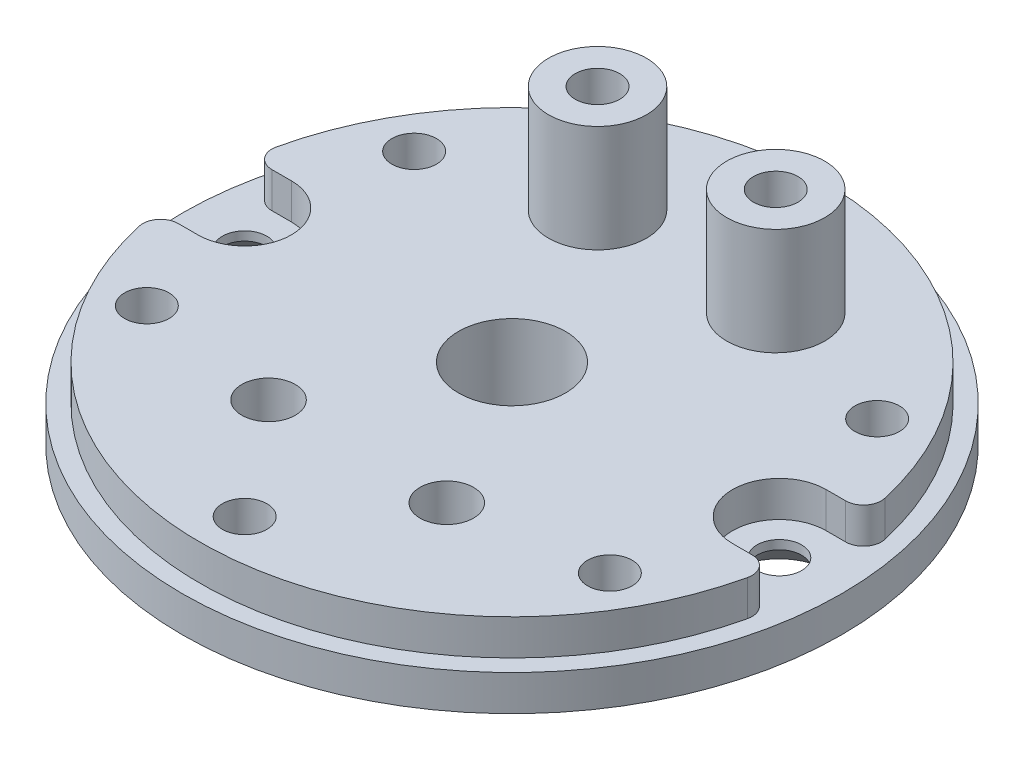
SolidWorks part; units mm, degrees
material "AISI 1020 Steel, Cold Rolled"
ref_plane "Front" through (0, 0, 0) normal (0, 0, 1) x (1, 0, 0)
ref_plane "Top" through (0, 0, 0) normal (0, 1, 0) x (1, 0, 0)
ref_plane "Right" through (0, 0, 0) normal (1, 0, 0) x (0, 0, -1)
sketch "Sketch1" plane through (0, 0, 0) normal (0, 1, 0) x (1, 0, 0)
  circle A0 centre (0, 0) radius 18.5
  dimension "D1" = 37
extrude "Boss-Extrude1" add sketch "Sketch1" along normal blind 2
sketch "Sketch2" plane through (0, 2, 0) normal (0, 1, 0) x (1, 0, 0)
  circle A0 centre (0, 0) radius 17.5
  dimension "D1" = 35
extrude "Boss-Extrude2" add sketch "Sketch2" along normal blind 2
sketch "Sketch3" plane through (0, 0, 0) normal (0, -1, 0) x (1, 0, 0)
  circle A0 centre (0, 0) radius 6
  dimension "D1" = 12
extrude "Boss-Extrude3" add sketch "Sketch3" along normal offset from surface (5 mm away) 9 up to face at (0, 4, 17.5)
sketch "Sketch4" plane through (0, -5, 0) normal (0, -1, 0) x (1, 0, 0)
  circle A0 centre (0, 0) radius 3
  dimension "D1" = 6
extrude "Cut-Extrude1" cut sketch "Sketch4" against normal up to next
sketch "Sketch5" plane through (0, 4, 0) normal (0, 1, 0) x (1, 0, 0)
  line L0 (-15, 2.625) -> (-17.625, 2.625)
  line L1 (-17.625, 2.625) -> (-17.625, -2.625)
  line L2 (-17.625, -2.625) -> (-15, -2.625)
  circle A0 centre (-15, 0) radius 2.625
  circle M5 centre (0, 0) radius 17.5
  dimension "D1" = 5.25
  dimension "D3" = 15
extrude "Cut-Extrude4" cut sketch "Sketch5" against normal up to surface (2 mm away) contours A0 M5 | A0 M5 | A0 L0 M5 | A0 L0 L1 M5 | A0 L2 M5 | A0 L1 L2 M5
fillet "Fillet1" radius 1 2 edges at (-17.302, 3, 2.625) (-17.302, 3, -2.625)
sketch "Sketch6" plane through (0, 2, 0) normal (0, 1, 0) x (1, 0, 0)
  circle A0 centre (-15, 0) radius 1.25
  arc A1 (-15, -2.625) -> (-15, 2.625) centre (-15, 0) ccw construction
  dimension "D1" = 2.5
extrude "Cut-Extrude5" cut sketch "Sketch6" against normal up to next
mirror "Mirror1" about plane through (0, 0, 0) normal (1, 0, 0) of "Cut-Extrude5", "Cut-Extrude4", "Fillet1"
chamfer "Chamfer1" distance 1.5 angle 45 2 edges at (15, 0, 1.25) (-15, 0, 1.25)
sketch "Sketch7" plane through (0, 0, 0) normal (0, -1, 0) x (1, 0, 0)
  circle A0 centre (0, 15) radius 1.25
  dimension "D1" = 2.5
  dimension "D2" = 15
extrude "Cut-Extrude6" cut sketch "Sketch7" against normal up to next
pattern_circular "CirPattern1" count 6 over 360 about axis through (0, 0, 0) along (0, 1, 0) of "Cut-Extrude6"
sketch "Sketch9" plane through (0, 4, 0) normal (0, 1, 0) x (1, 0, 0)
  circle A0 centre (-5, -8.6603) radius 1.5
  circle A1 centre (5, -8.6603) radius 1.5
  dimension "D4" = 3
  dimension "D1" = 10
  dimension "D2" = 10
  dimension "D3" = 10
extrude "Cut-Extrude7" cut sketch "Sketch9" against normal blind 3.5 contours A0 | A1
sketch "Sketch10" plane through (0, 4, 0) normal (0, 1, 0) x (1, 0, 0)
  circle A0 centre (-5, 9.798) radius 2.75
  circle A1 centre (5, 9.798) radius 2.75
  dimension "D4" = 5.5
  dimension "D1" = 10
  dimension "D2" = 11
  dimension "D3" = 11
extrude "Boss-Extrude4" add sketch "Sketch10" along normal offset from surface (6 mm away) 10 up to face at (11.9078, 0, 6.875)
sketch "Sketch11" plane through (0, 10, 0) normal (0, 1, 0) x (1, 0, 0)
  circle A0 centre (-5, 9.798) radius 1.25
  circle A1 centre (5, 9.798) radius 1.25
  dimension "D1" = 2.5
extrude "Cut-Extrude8" cut sketch "Sketch11" against normal up to surface (6 mm away) up to face at (5, 4, -7.048)
fillet "Fillet2" radius 0.25 2 edges at (0, 0, -6) (0, -5, 6)
chamfer "Chamfer2" distance 0.5 angle 45 1 edges at (0, -5, -3)
sketch "Sketch12" plane through (0, 0, 0) normal (0, -1, 0) x (1, 0, 0)
  line L0 (0, 0) -> (-15, 0) construction
  line L1 (0, 0) -> (0, 15) construction
  line L2 (-1.5, 12.9132) -> (-1.5, 7.3485) construction
  line L3 (-12.9132, 1.5) -> (-7.3485, 1.5) construction
  line L4 (-11.7367, 1.5) -> (-8.124, 1.5)
  line L5 (-1.5, 11.7367) -> (-1.5, 8.124)
  circle A0 centre (0, 0) radius 13 construction
  circle A1 centre (0, 0) radius 7.5 construction
  arc A2 (-12.7148, 2.7083) -> (-2.7083, 12.7148) centre (0, 0) cw
  arc A3 (-7.1683, 2.2059) -> (-2.2059, 7.1683) centre (0, 0) cw
  arc A4 (-1.5, 11.7367) -> (-2.7083, 12.7148) centre (-2.5, 11.7367) ccw
  arc A5 (-1.5, 8.124) -> (-2.2059, 7.1683) centre (-2.5, 8.124) cw
  arc A6 (-7.1683, 2.2059) -> (-8.124, 1.5) centre (-8.124, 2.5) cw
  arc A7 (-11.7367, 1.5) -> (-12.7148, 2.7083) centre (-11.7367, 2.5) cw
  dimension "D1" = 26
  dimension "D2" = 15
  dimension "D5" = 1
  dimension "D3" = 1.5
  dimension "D4" = 1.5
extrude "Cut-Extrude9" cut sketch "Sketch12" against normal blind 0.3
pattern_circular "CirPattern2" count 4 over 360 about axis through (0, 0, 0) along (0, 1, 0) of "Cut-Extrude9"
chamfer "Chamfer3" distance 0.25 angle 45 6 edges at (-11.9078, 0, -6.875) (0, 0, -13.75) (11.9078, 0, -6.875) (11.9078, 0, 6.875) (-11.9078, 0, 6.875) (0, 0, 13.75)
